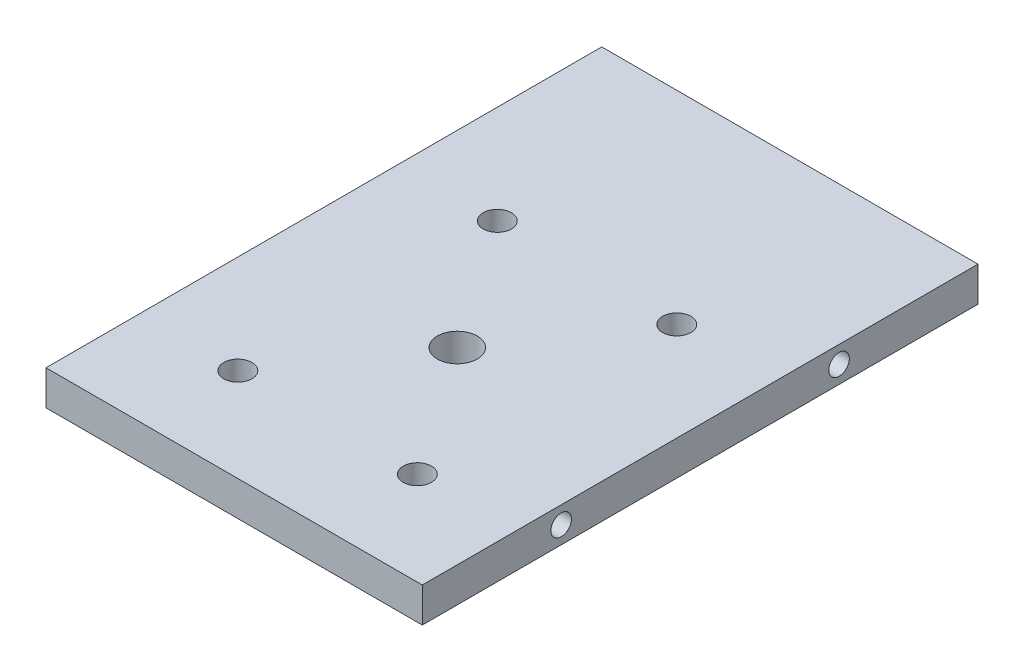
SolidWorks part; units mm, degrees
ref_plane "Front Plane" through (0, 0, 0) normal (0, 0, 1) x (1, 0, 0)
ref_plane "Top Plane" through (0, 0, 0) normal (0, 1, 0) x (1, 0, 0)
ref_plane "Right Plane" through (0, 0, 0) normal (1, 0, 0) x (0, 0, -1)
sketch "Sketch1" plane through (0, 0, 0) normal (0, 1, 0) x (1, 0, 0)
  line L1 (0, 0) -> (32.5, 0)
  line L2 (0, 0) -> (0, 48)
  line L3 (0, 48) -> (32.5, 48)
  line L4 (32.5, 0) -> (32.5, 48)
extrude "Boss-Extrude1" add sketch "Sketch1" along normal blind 3
sketch "Sketch2" plane through (0, 3, 0) normal (0, 1, 0) x (1, 0, 0)
  line L0 (0, 0) -> (0, 3)
  line L1 (0, 48) -> (0, 0) construction
  line L2 (0, 3) -> (32.5, 3)
  line L3 (32.5, 0) -> (32.5, 48) construction
  line L4 (0, 1.5) -> (32.5, 1.5)
  line L5 (16.25, 3) -> (0, 0)
  line L6 (16.25, 3) -> (32.5, 0)
  line L7 (0, 48) -> (0, 45)
  line L8 (0, 45) -> (32.5, 45)
  line L9 (0, 46.5) -> (32.5, 46.5)
  line L10 (0, 48) -> (16.25, 45)
  line L11 (16.25, 45) -> (32.5, 48)
sketch "Sketch4" plane through (0, 0, 0) normal (-1, 0, 0) x (0, 0, 1)
  line L0 (-48, 3) -> (-24, 0)
  line L1 (-48, 0) -> (0, 0) construction
  line L2 (-24, 0) -> (0, 3)
  line L3 (0, 3) -> (0, 0)
  line L4 (0, 0) -> (-24, 3)
  line L5 (-48, 3) -> (0, 3) construction
  line L6 (-24, 3) -> (-48, 0)
hole_wizard "#2-56 Tapped Hole1" positions "Sketch5" profile "Sketch6" tap size "#2-56" standard "ANSI Inch"
sketch "Sketch5" plane through (0, 0, 0) normal (-1, 0, 0) x (0, 0, 1)
  line L0 (-48, 3) -> (-24, 0) construction
  line L1 (-24, 0) -> (0, 3) construction
  point P0 (-36, 1.5)
  point P4 (-12, 1.5)
sketch "Sketch6" plane through (0, 1.5, -36) normal (0, 1, 0) x (0, 0, 1)
  line L0 (0, 0) -> (0, 8)
  line L1 (0, 8) -> (0.889, 7.4658)
  line L2 (0.889, 7.4658) -> (0.889, 0)
  line L5 (0.889, 0) -> (0, 0)
  line L10 (0, 8) -> (-0.889, 7.4658) construction
  line L11 (0, -6.35) -> (0, 107.95) construction
  dimension "Tap Drill Dia." = 1.778
  dimension "Tap Drill Depth" = 8
  dimension "Drill Angle" = 118
cosmetic thread "Hole Thread1" parameters "D1"=4.37, "D2"=2.1844
cosmetic thread "Hole Thread2" parameters "D1"=4.37, "D2"=2.1844
sketch "Sketch7" plane through (32.5, 0, 0) normal (1, 0, 0) x (0, 0, -1)
  line L0 (0, 3) -> (24, 0)
  line L1 (0, 0) -> (48, 0) construction
  line L2 (24, 0) -> (48, 3)
  line L3 (48, 3) -> (48, 0)
  line L4 (48, 0) -> (24, 3)
  line L5 (0, 3) -> (48, 3) construction
  line L6 (24, 3) -> (0, 0)
hole_wizard "#2-56 Tapped Hole2" positions "Sketch8" profile "Sketch9" tap size "#2-56" standard "ANSI Inch"
sketch "Sketch8" plane through (32.5, 0, 0) normal (1, 0, 0) x (0, 0, -1)
  line L0 (0, 3) -> (24, 0) construction
  line L1 (24, 0) -> (48, 3) construction
  point P0 (12, 1.5)
  point P4 (36, 1.5)
sketch "Sketch9" plane through (32.5, 1.5, -12) normal (0, 1, 0) x (0, 0, -1)
  line L0 (0, 0) -> (0, 8)
  line L1 (0, 8) -> (0.889, 7.4658)
  line L2 (0.889, 7.4658) -> (0.889, 0)
  line L5 (0.889, 0) -> (0, 0)
  line L10 (0, 8) -> (-0.889, 7.4658) construction
  line L11 (0, -6.35) -> (0, 107.95) construction
  dimension "Tap Drill Dia." = 1.778
  dimension "Tap Drill Depth" = 8
  dimension "Drill Angle" = 118
cosmetic thread "Hole Thread3" parameters "D1"=4.37, "D2"=2.1844
cosmetic thread "Hole Thread4" parameters "D1"=4.37, "D2"=2.1844
sketch "Sketch12" plane through (0, 3, 0) normal (0, 1, 0) x (1, 0, 0)
  line L0 (0, 0) -> (0, 19.275)
  line L1 (0, 48) -> (0, 0) construction
  line L2 (0, 19.275) -> (32.5, 19.275)
  line L3 (32.5, 0) -> (32.5, 48) construction
hole_wizard "#8-32 Tapped Hole1" positions "Sketch13" profile "Sketch14" tap size "#8-32" standard "ANSI Inch"
sketch "Sketch13" plane through (0, 3, 0) normal (0, 1, 0) x (1, 0, 0)
  line L0 (0, 19.275) -> (32.5, 19.275) construction
  point P0 (16.25, 19.275)
sketch "Sketch14" plane through (16.25, 3, -19.275) normal (1, 0, 0) x (0, 0, 1)
  line L0 (0, 0) -> (0, 10.71)
  line L1 (0, 10.71) -> (1.7272, 9.6722)
  line L2 (1.7272, 9.6722) -> (1.7272, 0)
  line L5 (1.7272, 0) -> (0, 0)
  line L10 (0, 10.71) -> (-1.7272, 9.6722) construction
  line L11 (0, -6.35) -> (0, 107.95) construction
  dimension "Tap Drill Dia." = 3.4544
  dimension "Tap Drill Depth" = 10.71
  dimension "Drill Angle" = 118
cosmetic thread "Hole Thread5" parameters "D1"=8.33, "D2"=4.1656
sketch "Sketch15" plane through (0, 3, 0) normal (0, 1, 0) x (1, 0, 0)
  line L0 (16.25, 19.275) -> (25.5, 19.275)
  line L1 (0, 19.275) -> (32.5, 19.275) construction
  line L2 (25.5, 19.275) -> (25.5, 31.98)
  line L3 (25.5, 31.98) -> (7, 31.98)
  line L4 (7, 31.98) -> (7, 6.57)
  line L5 (7, 6.57) -> (25.5, 6.57)
  line L6 (25.5, 6.57) -> (25.5, 19.275)
  line L7 (7, 31.98) -> (7, 30.48)
  line L8 (7, 30.48) -> (25.5, 30.48)
  line L9 (7, 31.98) -> (8.5, 31.98)
  line L10 (8.5, 31.98) -> (8.5, 6.57)
  line L11 (25.5, 31.98) -> (24, 31.98)
  line L12 (24, 31.98) -> (24, 6.57)
  line L13 (25.5, 6.57) -> (25.5, 8.07)
  line L14 (25.5, 8.07) -> (7, 8.07)
sketch "Sketch16" plane through (0, 3, 0) normal (0, 1, 0) x (1, 0, 0)
  line L1 (7, 30.48) -> (25.5, 30.48) construction
  line L2 (8.5, 31.98) -> (8.5, 6.57) construction
  line L4 (24, 31.98) -> (24, 6.57) construction
  line L6 (25.5, 8.07) -> (7, 8.07) construction
  circle A0 centre (8.5, 30.48) radius 1.22
  circle A1 centre (24, 30.48) radius 1.22
  circle A2 centre (8.5, 8.07) radius 1.22
  circle A3 centre (24, 8.07) radius 1.22
extrude "Cut-Extrude4" cut sketch "Sketch16" against normal blind 3
